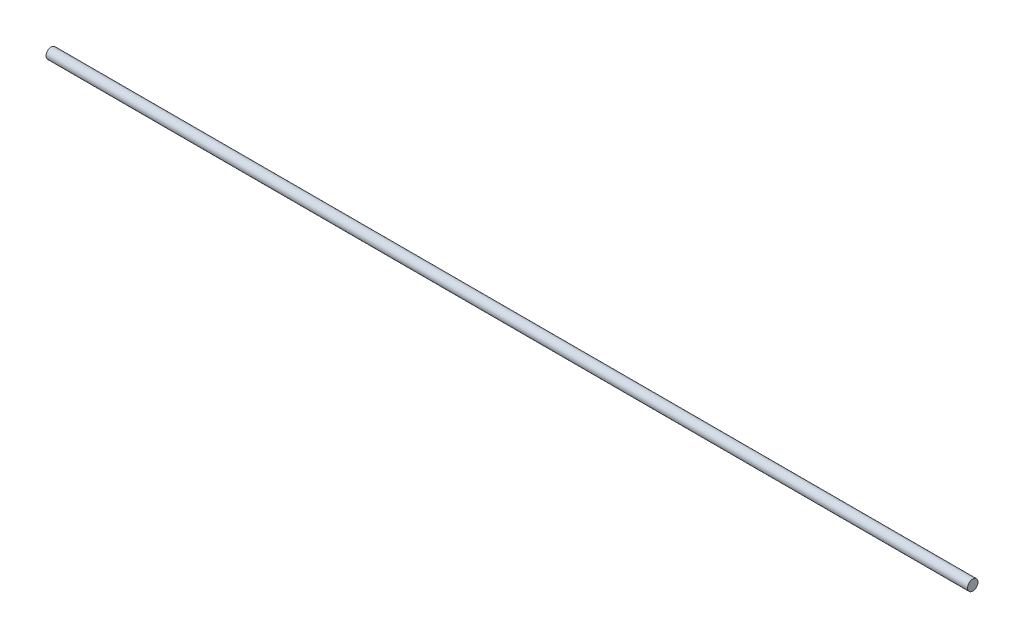
SolidWorks part; units mm, degrees
ref_plane "Front Plane" through (0, 0, 0) normal (0, 0, 1) x (1, 0, 0)
ref_plane "Top Plane" through (0, 0, 0) normal (0, 1, 0) x (1, 0, 0)
ref_plane "Right Plane" through (0, 0, 0) normal (1, 0, 0) x (0, 0, -1)
sketch "Sketch3" plane through (0, 0, 0) normal (1, 0, 0) x (0, 0, -1)
  circle A0 centre (0, 0) radius 6.35
  dimension "D1" = 12.7
extrude "Boss-Extrude1" add sketch "Sketch3" along normal blind 1122.1376
equation "\"F\"= 400'Force"
equation "\"E\"= 10000000'Young's Modulus"
equation "\"delta\"= 0.009in'Maximum Axial Deflection"
equation "\"d\"= 0.5'Diameter"
equation "\"A\"= ( pi / 4 ) * ( \"d\" ^ 2 )'Cross-Sectional Area"
equation "\"L\"= ( \"delta\" * \"A\" * \"E\" ) / \"F\"'Bar Length"
equation "\"D1@Sketch3\"=\"d\""
equation "\"D1@Boss-Extrude1\"=\"L\""
